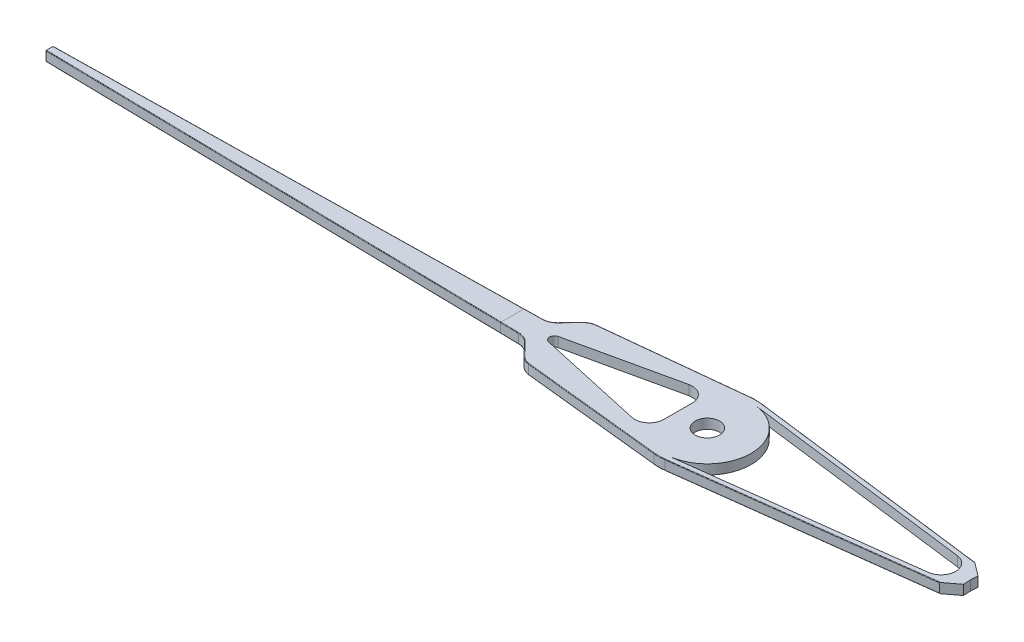
SolidWorks part; units mm, degrees
ref_plane "Front" through (0, 0, 0) normal (0, 0, 1) x (1, 0, 0)
ref_plane "Top" through (0, 0, 0) normal (0, 1, 0) x (1, 0, 0)
ref_plane "Right" through (0, 0, 0) normal (1, 0, 0) x (0, 0, -1)
sketch "Sketch1" plane through (0, 0, 0) normal (0, 1, 0) x (1, 0, 0)
  line L0 (-13.5, 0) -> (5.4, 0) construction
  line L1 (-13.5, -0.075) -> (-13.5, 0.075)
  line L2 (-13.5, 0.075) -> (-3.6242, 0.2474)
  line L3 (-3.4137, 0.3389) -> (-3.1587, 0.6029)
  line L4 (-2.9743, 0.6929) -> (-0.1045, 0.9945)
  line L5 (0.1251, 0.9921) -> (5.1269, 0.3614)
  line L6 (5.1269, 0.3614) -> (5.4057, 0.1499)
  line L7 (5.4057, 0.1499) -> (5.4, 0)
  line L8 (5.4057, -0.1499) -> (5.4, 0)
  line L9 (5.1269, -0.3614) -> (5.4057, -0.1499)
  line L10 (0.1251, -0.9921) -> (5.1269, -0.3614)
  line L11 (-2.9743, -0.6929) -> (-0.1045, -0.9945)
  line L12 (-3.4137, -0.3389) -> (-3.1587, -0.6029)
  line L13 (-13.5, -0.075) -> (-3.6242, -0.2474)
  line L14 (-3.1596, 0.0976) -> (-0.9649, 0.5842)
  line L15 (-0.6, 0.2913) -> (-0.6, -0.2913)
  line L16 (-0.9649, -0.5842) -> (-3.1596, -0.0976)
  line L17 (0.1141, 0.8927) -> (4.8335, 0.2976)
  line L18 (4.8335, -0.2976) -> (0.1141, -0.8927)
  arc A0 (0.1251, 0.9921) -> (-0.1045, 0.9945) centre (0, 0) ccw
  arc A1 (0.1251, -0.9921) -> (-0.1045, -0.9945) centre (0, 0) cw
  arc A2 (-3.1587, 0.6029) -> (-2.9743, 0.6929) centre (-2.9429, 0.3945) cw
  arc A3 (-3.6242, 0.2474) -> (-3.4137, 0.3389) centre (-3.6295, 0.5473) ccw
  arc A4 (-2.9743, -0.6929) -> (-3.1587, -0.6029) centre (-2.9429, -0.3945) cw
  arc A5 (-3.4137, -0.3389) -> (-3.6242, -0.2474) centre (-3.6295, -0.5473) ccw
  arc A6 (-0.6, -0.2913) -> (-0.9649, -0.5842) centre (-0.9, -0.2913) cw
  arc A7 (-0.9649, 0.5842) -> (-0.6, 0.2913) centre (-0.9, 0.2913) cw
  arc A8 (-3.1596, 0.0976) -> (-3.1596, -0.0976) centre (-3.138, 0) ccw
  arc A9 (0.1141, -0.8927) -> (0.1141, 0.8927) centre (0, 0) ccw
  arc A10 (4.8335, 0.2976) -> (4.8335, -0.2976) centre (4.7959, 0) cw
  point P10 (-0.6, 0)
  point P28 (-3.0829, 0.6815)
  point P31 (-3.5, 0.2496)
  point P34 (-3.0829, -0.6815)
  point P37 (-3.5, -0.2496)
  point P39 (-3.6, 0)
  point P52 (7.1939, 0)
  dimension "D11" = 2
  dimension "D13" = 0.3
  dimension "D14" = 0.3
  dimension "D18" = 0.3
  dimension "D19" = 0.1
  dimension "D21" = 1.8
  dimension "D22" = 0.3
  dimension "D1" = 13.5
  dimension "D2" = 5.4
  dimension "D3" = 0.075
  dimension "D4" = 91
  dimension "D5" = 3.5
  dimension "D6" = 0.15
  dimension "D7" = 125
  dimension "D8" = 0.35
  dimension "D9" = 140
  dimension "D10" = 150
  dimension "D12" = 45
  dimension "D15" = 0.6
  dimension "D16" = 25
  dimension "D17" = 3
extrude "Boss-Extrude1" add sketch "Sketch1" along normal mid plane 0.2
sketch "Sketch2" plane through (0, 0.1, 0) normal (0, 1, 0) x (1, 0, 0)
  circle A0 centre (0, 0) radius 0.25
  dimension "D1" = 0.5
extrude "Cut-Extrude1" cut sketch "Sketch2" against normal through all
fillet "Fillet1" radius 0.01 31 edges at (2.626, 0.1, 0.6768) (0.0104, 0.1, 0.9999) (-1.5394, 0.1, 0.8437) (-3.0744, 0.1, 0.6642) (-3.2862, 0.1, 0.4709) (-3.5099, 0.1, 0.2722) (-8.5621, 0.1, 0.1612) (-13.5, 0.1, 0) (-8.5621, 0.1, -0.1612) (-3.5099, 0.1, -0.2722) (-3.2862, 0.1, -0.4709) (-3.0744, 0.1, -0.6642) (-1.5394, 0.1, -0.8437) (0.0104, 0.1, -0.9999) (2.626, 0.1, -0.6768) (2.626, -0.1, -0.6768) (0.0104, -0.1, -0.9999) (-1.5394, -0.1, -0.8437) (-3.0744, -0.1, -0.6642) (-3.2862, -0.1, -0.4709) (-3.5099, -0.1, -0.2722) (-8.5621, -0.1, -0.1612) (-13.5, -0.1, 0) (-8.5621, -0.1, 0.1612) (-3.5099, -0.1, 0.2722) (-3.2862, -0.1, 0.4709) (-3.0744, -0.1, 0.6642) (-1.5394, -0.1, 0.8437) (0.0104, -0.1, 0.9999) (2.626, -0.1, 0.6768) (-13.5, 0, -0.075)
sketch "Sketch3" plane through (0, 0.1, 0) normal (0, 1, 0) x (1, 0, 0)
  line L0 (-4, 2.4395) -> (-4, -2.0363)
  dimension "D1" = 4
split line "Split Line1"
